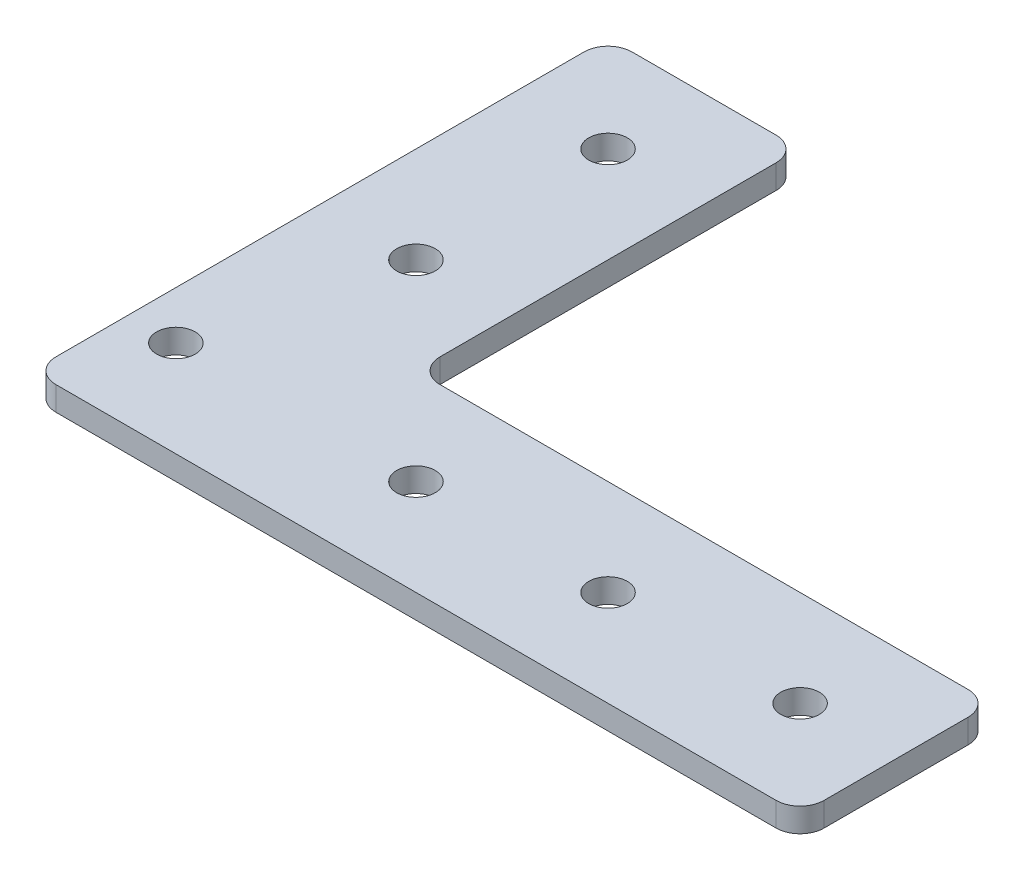
SolidWorks part; units mm, degrees
material "6061 Alloy"
ref_plane "Front" through (0, 0, 0) normal (0, 0, 1) x (1, 0, 0)
ref_plane "Top" through (0, 0, 0) normal (0, 1, 0) x (1, 0, 0)
ref_plane "Right" through (0, 0, 0) normal (1, 0, 0) x (0, 0, -1)
sketch "Sketch1" plane through (0, 0, 0) normal (0, 1, 0) x (1, 0, 0)
  line L0 (0, 0) -> (0, 76.2)
  line L1 (0, 76.2) -> (25.4, 76.2)
  line L2 (25.4, 76.2) -> (101.6, 25.4)
  line L3 (101.6, 25.4) -> (101.6, 0)
  line L4 (101.6, 0) -> (0, 0)
  dimension "D1" = 76.2
  dimension "D2" = 25.4
  dimension "D3" = 25.4
  dimension "D4" = 76.2
extrude "Boss-Extrude1" add sketch "Sketch1" along normal blind 3.175
hole_wizard "#10 Clearance Hole1" positions "Sketch2" profile "Sketch3" hole size "#10" standard "ANSI Inch" end condition through all
sketch "Sketch2" plane through (0, 3.175, 0) normal (0, 1, 0) x (1, 0, 0)
  line L1 (25.4, 76.2) -> (0, 76.2) construction
  line L4 (101.6, 12.7) -> (12.7, 12.7) construction
  line L5 (101.6, 0) -> (101.6, 25.4) construction
  line L6 (12.7, 12.7) -> (12.7, 76.2) construction
  point P10 (12.7, 63.5)
  point P12 (12.7, 38.1)
  point P16 (38.1, 12.7)
  point P18 (63.5, 12.7)
  point P20 (88.9, 12.7)
  dimension "D1" = 12.7
  dimension "D2" = 25.4
  dimension "D3" = 25.4
  dimension "D5" = 25.4
  dimension "D6" = 12.7
sketch "Sketch3" plane through (88.9, 3.175, -12.7) normal (1, 0, 0) x (0, 0, 1)
  line L0 (0, 0) -> (0, 3.175)
  line L1 (0, 3.175) -> (2.5527, 3.175)
  line L2 (2.5527, 3.175) -> (2.5527, 0)
  line L5 (2.5527, 0) -> (0, 0)
  line L11 (0, -6.35) -> (0, 107.95) construction
  dimension "Thru Hole Dia." = 5.1054
  dimension "Thru Hole Depth" = 3.175
hole_wizard "#10 Clearance Hole4" positions "Sketch4" profile "Sketch5" hole size "#10" standard "ANSI Inch" end condition through all
sketch "Sketch4" plane through (0, 3.175, 0) normal (0, 1, 0) x (1, 0, 0)
  line L0 (0, 12.7) -> (6.35, 12.7) construction
  line L1 (0, 76.2) -> (0, 0) construction
  line L2 (6.35, 12.7) -> (6.35, 0) construction
  line L3 (0, 0) -> (101.6, 0) construction
  point P2 (6.35, 12.7)
  dimension "D1" = 6.35
  dimension "D2" = 12.7
sketch "Sketch5" plane through (6.35, 3.175, -12.7) normal (1, 0, 0) x (0, 0, 1)
  line L0 (0, 0) -> (0, 3.175)
  line L1 (0, 3.175) -> (2.5527, 3.175)
  line L2 (2.5527, 3.175) -> (2.5527, 0)
  line L5 (2.5527, 0) -> (0, 0)
  line L11 (0, -6.35) -> (0, 107.95) construction
  dimension "Thru Hole Dia." = 5.1054
  dimension "Thru Hole Depth" = 3.175
sketch "Sketch6" plane through (0, 3.175, 0) normal (0, 1, 0) x (1, 0, 0)
  line L0 (25.4, 76.2) -> (25.4, 25.4)
  line L1 (25.4, 25.4) -> (101.6, 25.4)
  line L2 (101.6, 25.4) -> (25.4, 76.2)
extrude "Cut-Extrude1" cut sketch "Sketch6" against normal through all
fillet "Fillet1" radius 3.175 6 edges at (25.4, 1.5875, -25.4) (0, 1.5875, 0) (101.6, 1.5875, 0) (101.6, 1.5875, -25.4) (25.4, 1.5875, -76.2) (0, 1.5875, -76.2)
